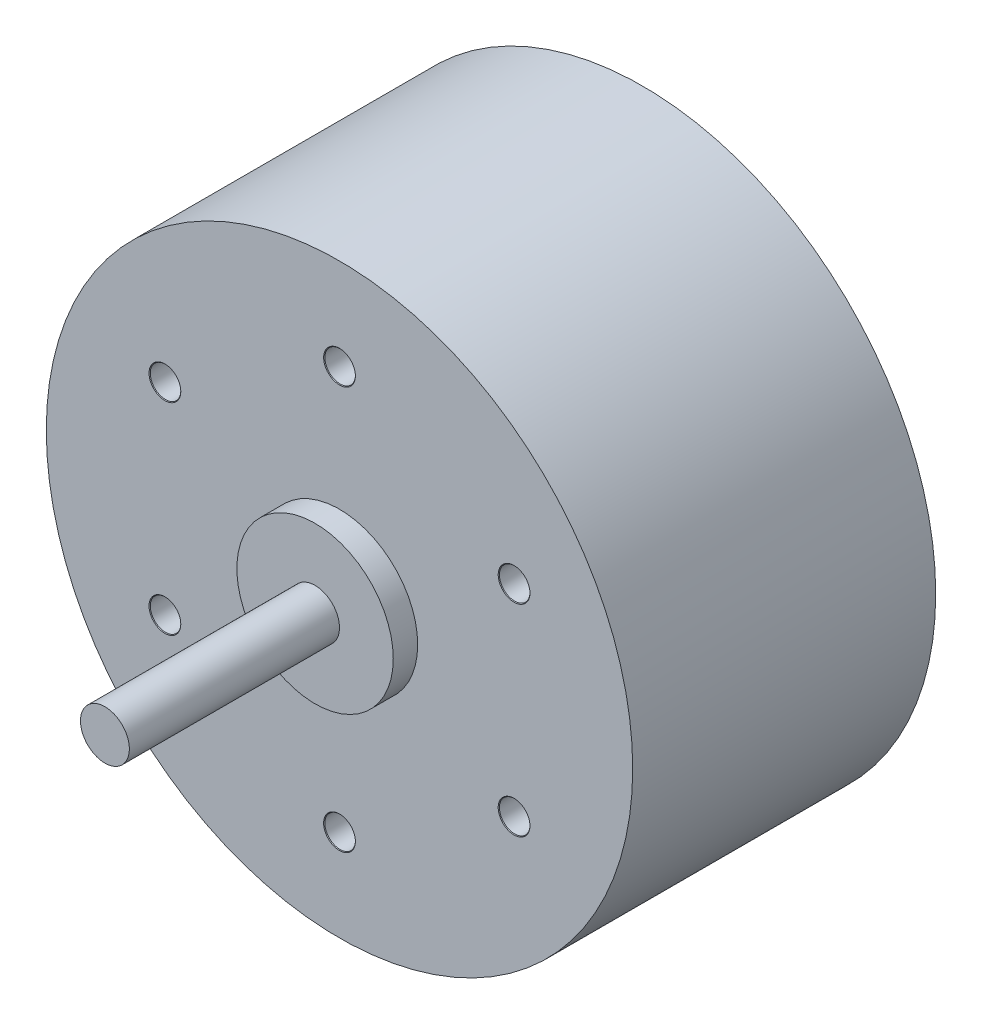
SolidWorks part; units mm, degrees
ref_plane "前基準面" through (0, 0, 0) normal (0, 0, 1) x (1, 0, 0)
ref_plane "上基準面" through (0, 0, 0) normal (0, 1, 0) x (1, 0, 0)
ref_plane "右基準面" through (0, 0, 0) normal (1, 0, 0) x (0, 0, -1)
sketch "草圖2" plane through (0, 0, 0) normal (0, 0, -1) x (-1, 0, 0)
  circle A0 centre (0, 0) radius 12
  dimension "D1" = 24
extrude "填料-伸長2" add sketch "草圖2" along normal blind 12.4
sketch "草圖5" plane through (0, 0, 0) normal (0, 0, 1) x (1, 0, 0)
  circle A0 centre (0, 0) radius 3.2
  dimension "D1" = 6.4
extrude "填料-伸長4" add sketch "草圖5" along normal blind 1
sketch "草圖3" plane through (0, 0, 1) normal (0, 0, 1) x (1, 0, 0)
  circle A0 centre (0, 0) radius 1
  dimension "D1" = 2
extrude "填料-伸長3" add sketch "草圖3" along normal blind 8.6
sketch "草圖6" plane through (0, 0, -12.4) normal (0, 0, -1) x (-1, 0, 0)
  circle A0 centre (0, 0) radius 3
  dimension "D1" = 6
extrude "填料-伸長5" add sketch "草圖6" along normal blind 0.7
sketch "草圖7" plane through (0, 0, 0) normal (0, 0, 1) x (1, 0, 0)
  line L0 (0, 0) -> (0, 8.25) construction
  line L1 (0, 0) -> (7.1447, 4.125) construction
  circle A0 centre (0, 0) radius 8.25 construction
  point P3 (0, 8.25)
  point P4 (7.1447, 4.125)
  point P7 (7.1447, -4.125)
  point P8 (0, -8.25)
  point P9 (-7.1447, -4.125)
  point P10 (-7.1447, 4.125)
  dimension "D1" = 16.5
  dimension "D2" = 6
  dimension "D3" = 60
hole_wizard "M1.6  螺絲攻的螺孔鑽1" positions "草圖8" profile "草圖9" hole size "M1.6" standard "ISO"
sketch "草圖8" plane through (0, 0, 0) normal (0, 0, 1) x (1, 0, 0)
  line L0 (0, 0) -> (0, 8.25) construction
  line L1 (0, 0) -> (7.1447, 4.125) construction
  circle A0 centre (0, 0) radius 8.25
  point P0 (0, 8.25)
  point P15 (7.1447, 4.125)
  point P16 (7.1447, -4.125)
  point P17 (0, -8.25)
  point P18 (-7.1447, -4.125)
  point P19 (-7.1447, 4.125)
  dimension "D1" = 16.5
  dimension "D3" = 60
  dimension "D2" = 6
sketch "草圖9" plane through (0, 8.25, 0) normal (1, 0, 0) x (0, -1, 0)
  line L0 (0, 0) -> (0, 2.3755)
  line L1 (0, 2.3755) -> (0.625, 2)
  line L2 (0.625, 2) -> (0.625, 0.025)
  line L3 (0.625, 0.025) -> (0.65, 0)
  line L5 (0.65, 0) -> (0, 0)
  line L6 (-0.625, 0.025) -> (-0.65, 0) construction
  line L10 (0, 2.3755) -> (-0.625, 2) construction
  line L11 (0, -6.35) -> (0, 107.95) construction
  dimension "鑽孔直徑" = 1.25
  dimension "鑽孔深度" = 2
  dimension "近端錐孔直徑" = 1.3
  dimension "近端錐孔角度" = 90
  dimension "導頭角度" = 118
